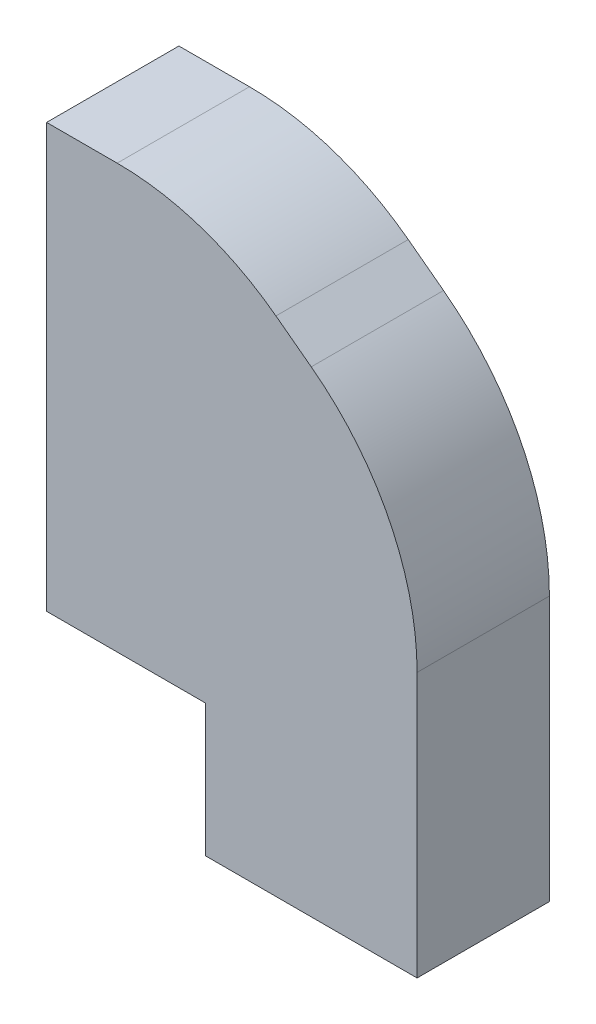
SolidWorks part; units mm, degrees
material "PBT General Purpose"
ref_plane "Front Plane" through (0, 0, 0) normal (0, 0, 1) x (1, 0, 0)
ref_plane "Top Plane" through (0, 0, 0) normal (0, 1, 0) x (1, 0, 0)
ref_plane "Right Plane" through (0, 0, 0) normal (1, 0, 0) x (0, 0, -1)
sketch "frame_outline" plane through (0, 0, 0) normal (0, 0, 1) x (1, 0, 0)
  line L0 (0, 0) -> (0.3, 0)
  line L1 (0.3, 0) -> (0.3, -0.25)
  line L2 (0.3, -0.25) -> (0.7, -0.25)
  line L3 (0.7, -0.25) -> (0.7, -0.1287)
  line L84 (0.7, -0.1287) -> (0.7, 0.5)
  line L87 (0, 0.8) -> (0, 0)
  line L88 (0, 0.8) -> (0.3, 0.8)
  line L89 (0.3, 0.8) -> (0.7, 0.5)
  dimension "D1" = 0.8
  dimension "D2" = 0.3
  dimension "D3" = 0.4
  dimension "D4" = 0.25
  dimension "D5" = 0.3
  dimension "D6" = 0.5
extrude "Boss-Extrude1" add sketch "frame_outline" along normal mid plane 0.25
fillet "Fillet1" radius 0.5 2 edges at (0.7, 0.5, 0) (0.3, 0.8, 0)
equation "\"t\"= 0.25'thickness of the sheets"
equation "\"t_cf\" = 0.115'thickness of single carbon fiber layer"
equation "\"t_kapton\" = 0.025'thickness of single Kapton flex layer"
equation "\"t_fr4\" = 0.1'thickness of FR4 with copper layer"
equation "\"joint_flex\"= 0.1'Width of flextures gap"
equation "\"joint_flex_eff\"= 0.02'Width of flecture after castelation"
equation "\"joint_fold\"= 0.2'Width of folding joints for 90deg fold"
equation "\"gap_tolerance\"= 0.002'Width to have interfecence fit between carbon fiber inserts"
equation "\"assemble_angle\"= 90'Angle of assembly parts"
equation "\"D1@Boss-Extrude1\"=\"t\""
equation "\"link_lift\"= 0.5'Actuation linkage amplification for the lift motion"
equation "\"link_swing\"= 0.45'Actuation linkage amplification for the swing motion"
equation "\"D4@frame_outline\"=\"t\""
